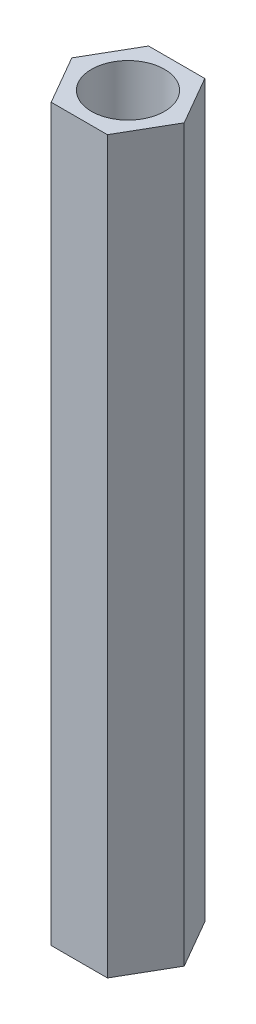
SolidWorks part; units mm, degrees
material "Brass"
ref_plane "Front Plane" through (0, 0, 0) normal (0, 0, 1) x (1, 0, 0)
ref_plane "Top Plane" through (0, 0, 0) normal (0, 1, 0) x (1, 0, 0)
ref_plane "Right Plane" through (0, 0, 0) normal (1, 0, 0) x (0, 0, -1)
sketch "Sketch1" plane through (0, 0, 0) normal (0, 1, 0) x (1, 0, 0)
  line L1 (2.3094, 0) -> (1.1547, 2)
  line L2 (1.1547, 2) -> (-1.1547, 2)
  line L3 (-1.1547, 2) -> (-2.3094, 0)
  line L4 (-2.3094, 0) -> (-1.1547, -2)
  line L5 (-1.1547, -2) -> (1.1547, -2)
  line L6 (1.1547, -2) -> (2.3094, 0)
  circle A0 centre (0, 0) radius 1.5
  circle A1 centre (0, 0) radius 2 construction
  dimension "D1" = 3
  dimension "D2" = 4
extrude "Boss-Extrude1" add sketch "Sketch1" along normal blind 30
